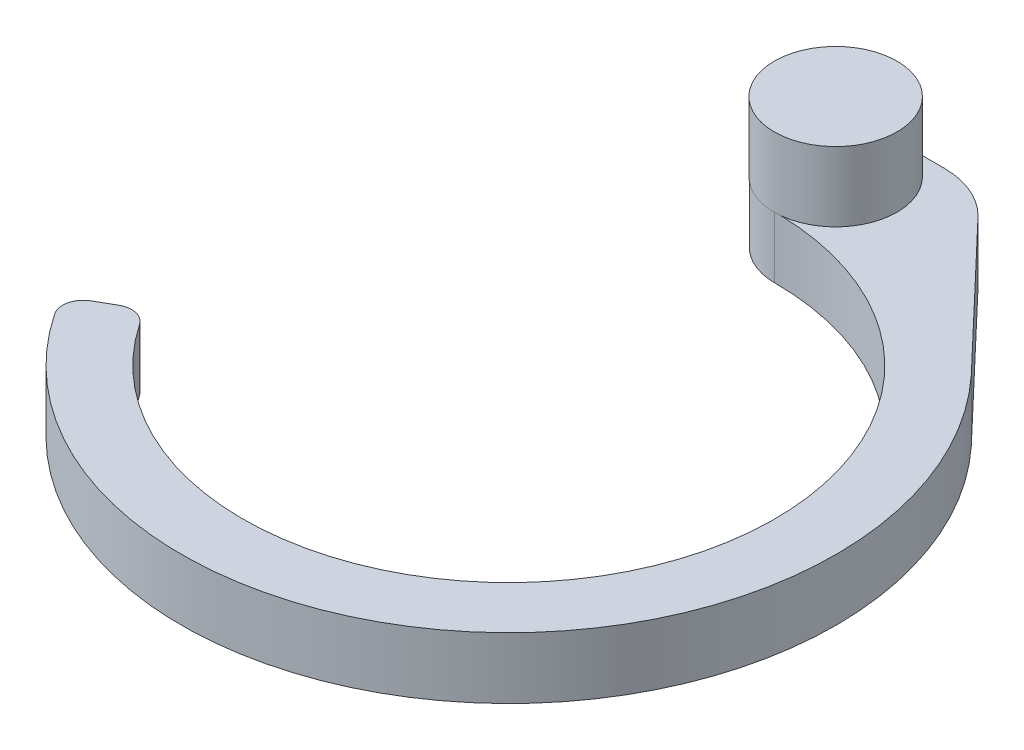
SolidWorks part; units mm, degrees
ref_plane "正面" through (0, 0, 0) normal (0, 0, 1) x (1, 0, 0)
ref_plane "平面" through (0, 0, 0) normal (0, 1, 0) x (1, 0, 0)
ref_plane "右側面" through (0, 0, 0) normal (1, 0, 0) x (0, 0, -1)
sketch "ｽｹｯﾁ2" plane through (0, 0, 0) normal (0, 1, 0) x (1, 0, 0)
  line L1 (-1.8089, 2.6033) -> (0, 0)
  line L2 (-60.4669, -34.9106) -> (-64.8074, -37.4166)
  line L4 (0, 95) -> (11.4274, 95)
  line L5 (25.9115, 88.7917) -> (58.5757, 54.4875)
  arc A0 (-66.4612, -44.5298) -> (57.2894, 55.8384) centre (0, 0) ccw
  arc A1 (-53.8264, -36.4378) -> (0, 65) centre (0, 0) ccw
  arc A2 (0, 95) -> (0, 65) centre (0, 80) ccw
  arc A3 (11.4274, 95) -> (25.9115, 88.7917) centre (11.4274, 75) cw
  arc A4 (-53.8264, -36.4378) -> (-60.4669, -34.9106) centre (-57.9669, -39.2407) ccw
  arc A5 (-66.4612, -44.5298) -> (-64.8074, -37.4166) centre (-62.3074, -41.7467) cw
  dimension "D1" = 160
  dimension "D2" = 130
  dimension "D4" = 20
  dimension "D5" = 5
  dimension "D6" = 5
extrude "ﾎﾞｽ - 押し出し4" add sketch "ｽｹｯﾁ2" along normal blind 15 contours A5 A0 L5 A3 L4 A2 A1 A4 L2
sketch "ｽｹｯﾁ10" plane through (0, 15, 0) normal (0, 1, 0) x (1, 0, 0)
  circle A0 centre (0, 79.9067) radius 15
  dimension "D1" = 30
extrude "ﾎﾞｽ - 押し出し5" add sketch "ｽｹｯﾁ10" along normal blind 17
